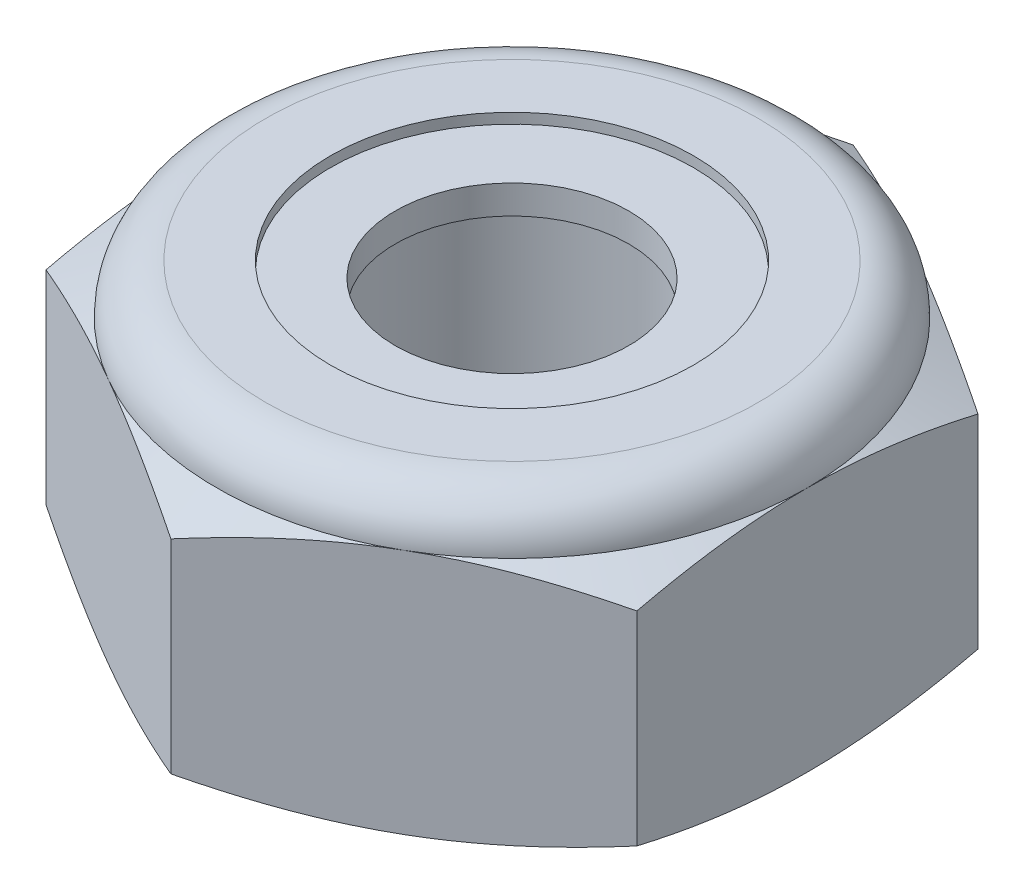
SolidWorks part; units mm, degrees
material "Plain Carbon Steel"
ref_plane "Front" through (0, 0, 0) normal (0, 0, 1) x (1, 0, 0)
ref_plane "Top" through (0, 0, 0) normal (0, 1, 0) x (1, 0, 0)
ref_plane "Right" through (0, 0, 0) normal (1, 0, 0) x (0, 0, -1)
sketch "Sketch1" plane through (0, 0, 0) normal (0, 1, 0) x (1, 0, 0)
  line L1 (0, 5.041) -> (-4.3656, 2.5205)
  line L2 (-4.3656, 2.5205) -> (-4.3656, -2.5205)
  line L3 (-4.3656, -2.5205) -> (0, -5.041)
  line L4 (0, -5.041) -> (4.3656, -2.5205)
  line L5 (4.3656, -2.5205) -> (4.3656, 2.5205)
  line L6 (4.3656, 2.5205) -> (0, 5.041)
  circle A0 centre (0, 0) radius 4.3656 construction
  dimension "Hex Flats" = 8.7312
extrude "Extrude1" add sketch "Sketch1" along normal blind 4.3656
sketch "Sketch2" plane through (0, 0, 0) normal (1, 0, 0) x (0, 0, -1)
  line L0 (-2.0828, 0) -> (-2.0828, 4.3656) construction
  line L1 (0, 0) -> (2.0828, 0)
  line L2 (0, 0) -> (0, 4.3656)
  line L3 (0, 4.3656) -> (2.0828, 4.3656)
  line L4 (2.0828, 0) -> (2.0828, 4.3656)
  line L5 (-2.5205, 4.3656) -> (2.5205, 4.3656) construction
  line L7 (0, -2.0828) -> (0, 0) construction
  dimension "Thread Dia" = 4.1656
revolve "Revolve1" add sketch "Sketch2" angle 360 about L7
sketch "Sketch3" plane through (0, 0, 0) normal (1, 0, 0) x (0, 0, -1)
  line L0 (2.0828, 4.3656) -> (-2.0828, 4.3656) construction
  line L1 (-2.0828, 4.3656) -> (-2.0828, 3.5719) construction
  line L2 (-2.0828, 3.5719) -> (2.0828, 4.3656) construction
  line L3 (2.0828, 4.3656) -> (2.1014, 4.2682) construction
  line L4 (2.1014, 4.2682) -> (2.2314, 3.5859)
  line L5 (2.2314, 3.5859) -> (1.7629, 3.7491)
  line L6 (1.7629, 3.7491) -> (1.7258, 3.9441)
  line L7 (1.7258, 3.9441) -> (2.1014, 4.2682)
  line L8 (1.7443, 3.8466) -> (2.1664, 3.927) construction
  line L9 (2.0828, 4.3656) -> (2.0828, 3.9111) construction
  line L10 (2.0828, 3.9111) -> (-2.0828, 3.1174) construction
  line L11 (-2.0828, 3.1174) -> (-2.0828, 3.5719) construction
  line L12 (-0.1622, 4.3656) -> (0.1622, 2.6628) construction
  line L13 (-2.0828, 0) -> (-2.0828, 4.3656) construction
  line L14 (0, 4.3656) -> (2.0828, 4.3656) construction
  line L15 (2.0828, 0) -> (2.0828, 4.3656) construction
  point P13 (0, 3.5142)
  dimension "D4" = 60
sketch "Sketch4" plane through (0, 0, 0) normal (1, 0, 0) x (0, 0, -1)
  line L0 (0, 4.3656) -> (2.0828, 4.3656)
  line L1 (2.0828, 4.3656) -> (1.7258, 4.1991)
  line L2 (1.7258, 4.1991) -> (1.7258, 0.1665)
  line L3 (1.7258, 0.1665) -> (2.0828, 0)
  line L4 (2.0828, 0) -> (0, 0)
  line L5 (0, 0) -> (0, 4.3656)
  line L6 (2.0828, 0) -> (2.0828, 4.3656) construction
  line L7 (0, 4.3656) -> (2.0828, 4.3656) construction
  line L8 (0, 0) -> (2.0828, 0) construction
  line L9 (0, 0) -> (0, 4.3656) construction
  line L10 (0, 4.3656) -> (0, 4.7596) construction
  dimension "D1" = 25
combine bodies "Combine1" operation type subtract main body 108 bodies to subtract 109
sketch "Sketch5" plane through (0, 0, 0) normal (1, 0, 0) x (0, 0, -1)
  line L0 (0, 0) -> (4.3656, 0)
  line L1 (4.3656, 0) -> (5.041, 0.3149)
  line L2 (5.041, 0.3149) -> (5.041, 3.3231)
  line L3 (5.041, 3.3231) -> (4.3656, 3.638)
  line L4 (3.638, 4.3656) -> (3.638, 5.6356)
  line L5 (3.638, 5.6356) -> (6.311, 5.6356)
  line L6 (6.311, 5.6356) -> (6.311, -1.27)
  line L7 (6.311, -1.27) -> (0, -1.27)
  line L8 (0, -1.27) -> (0, 0)
  line L9 (4.3656, 3.638) -> (4.3656, 0) construction
  line L10 (0, 0) -> (2.0828, 0) construction
  line L13 (5.041, 1.819) -> (6.311, 1.819) construction
  line L14 (5.041, 4.3656) -> (5.041, 0) construction
  line L15 (0, 0) -> (0, 5.6356) construction
  line L20 (0, 5.6356) -> (3.638, 5.6356) construction
  line L22 (0, 4.3656) -> (2.0828, 4.3656) construction
  arc A0 (4.3656, 3.638) -> (3.638, 4.3656) centre (3.638, 3.638) ccw
  dimension "D1" = 25
  dimension "D2" = 1.27
revolve "Cut-Revolve3" cut sketch "Sketch5" angle 360 about L15
sketch "Sketch6" plane through (0, 0, 0) normal (1, 0, 0) x (0, 0, -1)
  line L0 (0, 3.638) -> (4.2132, 3.638)
  line L1 (3.638, 4.2132) -> (2.6819, 4.2132)
  line L2 (0, 5.6356) -> (0, 3.638)
  line L3 (2.6819, 5.6356) -> (0, 5.6356)
  line L4 (0, 5.6356) -> (3.638, 5.6356) construction
  line L5 (0, 0) -> (0, 5.6356) construction
  line L6 (0, 5.6356) -> (0, 44.323) construction
  line L7 (2.6819, 4.2132) -> (2.6819, 5.6356)
  line L8 (3.638, 4.3656) -> (3.638, 4.2132) construction
  line L9 (2.6819, 4.2132) -> (1.7258, 4.2132) construction
  line L10 (1.7258, 4.2132) -> (1.7258, 4.1991) construction
  arc A0 (4.2132, 3.638) -> (3.638, 4.2132) centre (3.638, 3.638) ccw
  arc A1 (4.3656, 3.638) -> (3.638, 4.3656) centre (3.638, 3.638) ccw construction
  dimension "D1" = 0.1524
revolve "Cut-Revolve4" cut sketch "Sketch6" angle 360 about L6
sketch "Sketch7" plane through (0, 0, 0) normal (1, 0, 0) x (0, 0, -1)
  line L0 (1.7258, 3.7142) -> (4.1312, 3.7142)
  line L1 (3.638, 4.137) -> (1.7258, 4.137)
  line L2 (1.7258, 4.137) -> (1.7258, 3.7142)
  line L3 (1.7258, 3.7142) -> (0, 3.7142) construction
  line L4 (0, 3.7142) -> (0, 4.137) construction
  line L5 (0, 4.137) -> (1.7258, 4.137) construction
  line L6 (1.7258, 3.7142) -> (1.7258, 3.638) construction
  line L7 (0, 3.638) -> (4.2132, 3.638) construction
  line L8 (3.638, 4.137) -> (3.638, 4.2132) construction
  arc A0 (4.1312, 3.7142) -> (3.638, 4.137) centre (3.638, 3.638) ccw
  arc A2 (4.2132, 3.638) -> (3.638, 4.2132) centre (3.638, 3.638) ccw construction
  dimension "D1" = 0.0762
revolve "Revolve2" add sketch "Sketch7" angle 360 about L4
equation "\"D1@Sketch3\"=\"Thread Pitch@Sketch3\"/8"
equation "\"D2@Sketch3\"=\"Thread Pitch@Sketch3\"/4"
equation "\"D5@Sketch3\"=\"Thread Pitch@Sketch3\""
equation "\"D4@Sketch5\"=\"Height@Extrude1\"/6"
